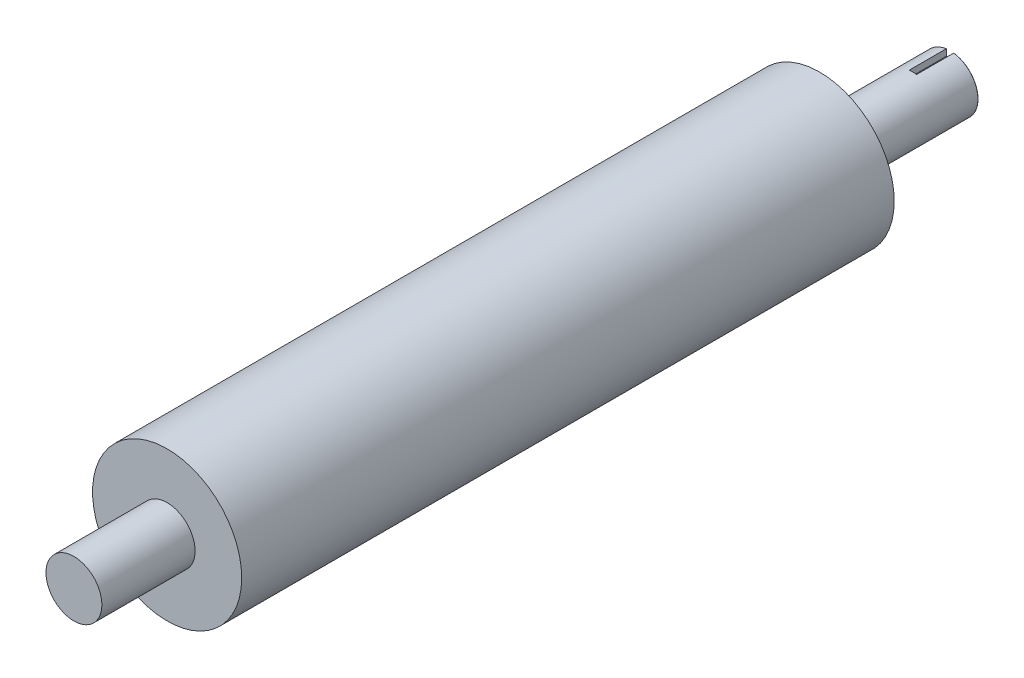
SolidWorks part; units mm, degrees
ref_plane "Front Plane" through (0, 0, 0) normal (0, 0, 1) x (1, 0, 0)
ref_plane "Top Plane" through (0, 0, 0) normal (0, 1, 0) x (1, 0, 0)
ref_plane "Right Plane" through (0, 0, 0) normal (1, 0, 0) x (0, 0, -1)
sketch "Sketch1" plane through (0, 0, 0) normal (0, 0, 1) x (1, 0, 0)
  circle A0 centre (0, 0) radius 40
  dimension "D1" = 80
extrude "Boss-Extrude1" add sketch "Sketch1" along normal blind 350
sketch "Sketch2" plane through (0, 0, 350) normal (0, 0, 1) x (1, 0, 0)
  circle A0 centre (0, 0) radius 15
  dimension "D1" = 30
extrude "Boss-Extrude2" add sketch "Sketch2" along normal blind 50
sketch "Sketch4" plane through (0, 0, 0) normal (0, 0, -1) x (-1, 0, 0)
  circle A0 centre (0, 0) radius 15
  dimension "D1" = 30
extrude "Boss-Extrude4" add sketch "Sketch4" along normal blind 70
sketch "Sketch5" plane through (0, 0, -70) normal (0, 0, -1) x (-1, 0, 0)
  line L0 (0, 0) -> (0, 24) construction
  line L1 (-2, 11.3248) -> (-2, 14.8661)
  line L2 (2, 11.3248) -> (2, 14.8661)
  circle A0 centre (0, 0) radius 15 construction
  arc A1 (2, 11.3248) -> (-2, 11.3248) centre (0, 0) ccw
  arc A2 (2, 14.8661) -> (-2, 14.8661) centre (0, 0) ccw
  dimension "D2" = 23
  dimension "D1" = 2
extrude "Cut-Extrude1" cut sketch "Sketch5" against normal blind 20
fillet "Fillet2" radius 0.1 1 edges at (0, -15, -70)
